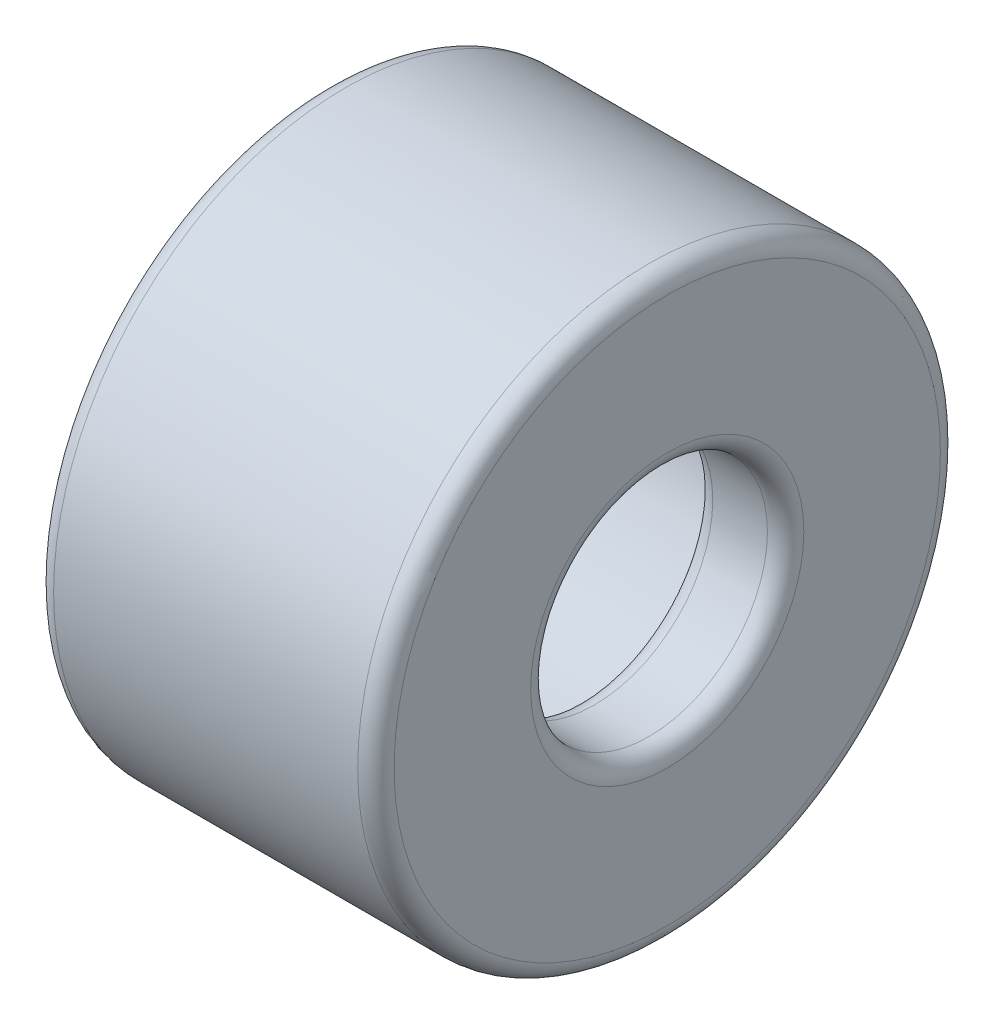
SolidWorks part; units mm, degrees
ref_plane "Front Plane" through (0, 0, 0) normal (0, 0, 1) x (1, 0, 0)
ref_plane "Top Plane" through (0, 0, 0) normal (0, 1, 0) x (1, 0, 0)
ref_plane "Right Plane" through (0, 0, 0) normal (1, 0, 0) x (0, 0, -1)
sketch "Sketch1" plane through (0, 0, 0) normal (0, 0, 1) x (1, 0, 0)
  line L0 (-1.1743, 0) -> (2.2457, 0) construction
  line L1 (11.3, 5) -> (-4.65, 5)
  line L2 (-4.65, 5) -> (-4.65, 8)
  line L3 (-4.65, 8) -> (-14, 8)
  line L4 (-14, 8) -> (-14, 0)
  line L5 (-14, 0) -> (11.3, 0)
  line L6 (11.3, 0) -> (11.3, 5)
  line L7 (4.65, 5.15) -> (4.65, 8)
  line L8 (4.65, 8) -> (14, 8)
  line L9 (14, 8) -> (14, 0)
  line L10 (14, 0) -> (11.5, 0)
  line L11 (11.5, 0) -> (11.5, 5.15)
  line L12 (11.5, 5.15) -> (4.65, 5.15)
  line L13 (-4.65, 8) -> (4.65, 8) construction
  line L14 (0, 0) -> (0, 8) construction
  dimension "D1" = 0.2
  dimension "D2" = 0.15
  dimension "D3" = 9.3
  dimension "D4" = 28
  dimension "D5" = 5
  dimension "D6" = 3
  dimension "D7" = 2.5
revolve "Revolve1" add sketch "Sketch1" angle 360 about L0
sketch "Sketch2" plane through (0, 0, 0) normal (1, 0, 0) x (0, 0, -1)
  circle A0 centre (0, 0) radius 3.25
  dimension "D1" = 6.5
extrude "Cut-Extrude1" cut sketch "Sketch2" against normal through all both and the other way through all
fillet "Fillet1" radius 0.5 5 edges at (14, 0, 8) (14, 0, -3.25) (11.5, 0, 3.25) (4.65, 0, 5.15) (4.65, 0, 8)
